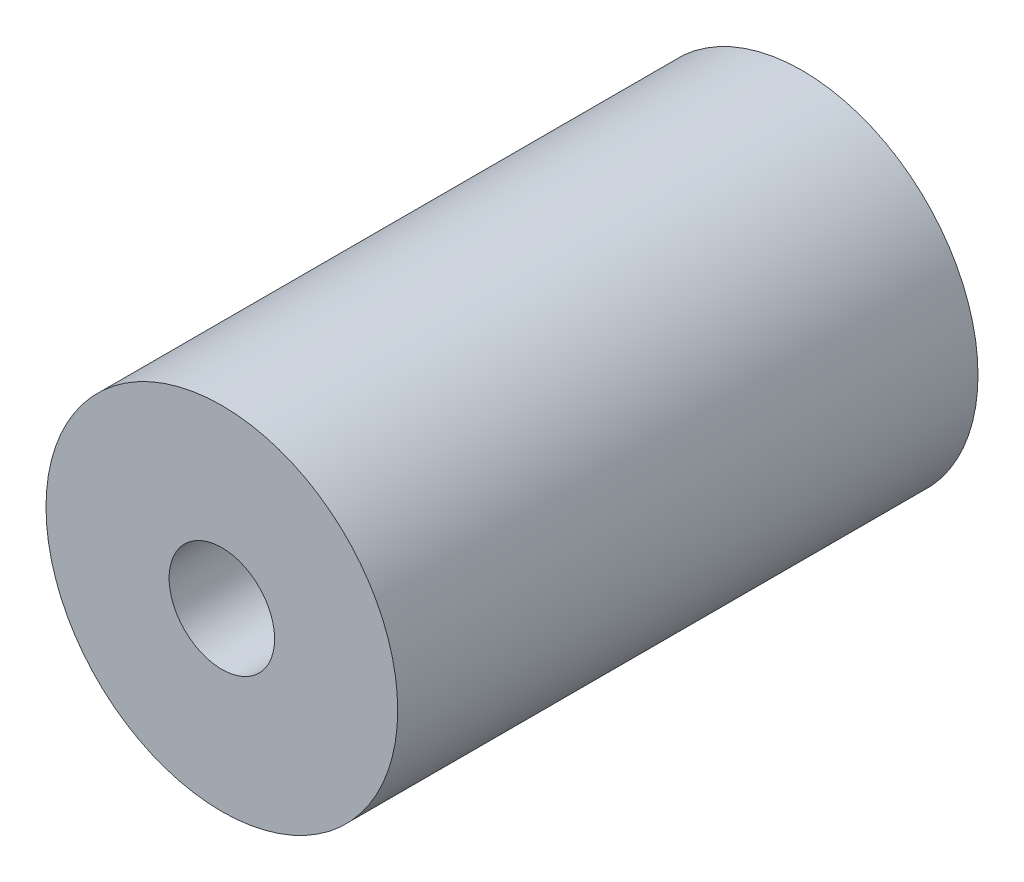
SolidWorks part; units mm, degrees
ref_plane "Front Plane" through (0, 0, 0) normal (0, 0, 1) x (1, 0, 0)
ref_plane "Top Plane" through (0, 0, 0) normal (0, 1, 0) x (1, 0, 0)
ref_plane "Right Plane" through (0, 0, 0) normal (1, 0, 0) x (0, 0, -1)
sketch "Sketch1" plane through (0, 0, 0) normal (0, 0, 1) x (1, 0, 0)
  circle A0 centre (0, 0) radius 10
  dimension "D1" = 20
extrude "Boss-Extrude1" add sketch "Sketch1" along normal blind 33
sketch "Sketch2" plane through (0, 0, 0) normal (0, 0, -1) x (-1, 0, 0)
  circle A0 centre (0, 0) radius 5
  dimension "D1" = 10
extrude "Cut-Extrude1" cut sketch "Sketch2" against normal blind 12
sketch "Sketch3" plane through (0, 0, 33) normal (0, 0, 1) x (1, 0, 0)
  circle A0 centre (0, 0) radius 3
  dimension "D1" = 6
extrude "Cut-Extrude2" cut sketch "Sketch3" against normal blind 13
